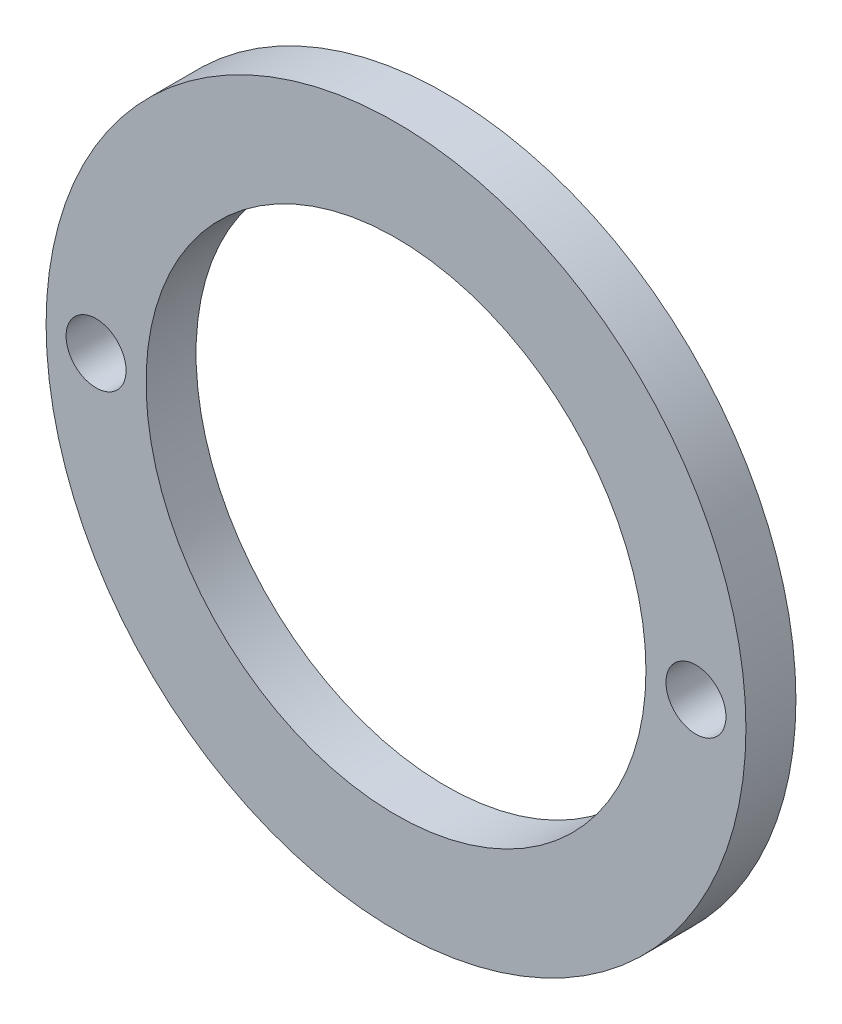
SolidWorks part; units mm, degrees
material "7075-T6 (SN)"
ref_plane "Front Plane" through (0, 0, 0) normal (0, 0, 1) x (1, 0, 0)
ref_plane "Top Plane" through (0, 0, 0) normal (0, 1, 0) x (1, 0, 0)
ref_plane "Right Plane" through (0, 0, 0) normal (1, 0, 0) x (0, 0, -1)
sketch "Sketch1" plane through (0, 0, 0) normal (0, 0, 1) x (1, 0, 0)
  circle A0 centre (0, 0) radius 7
  circle A1 centre (0, 0) radius 5
extrude "M10x0p5_Thin_Retaining_Nut" add sketch "Sketch1" along normal blind 1 from offset 1
sketch "Sketch2" plane through (0, 0, 0) normal (0, 0, 1) x (1, 0, 0)
  circle A0 centre (-6, 0) radius 0.6
  circle A1 centre (6, 0) radius 0.6
extrude "Two_Pin_Wrench_Holes_D1p2" cut sketch "Sketch2" against normal through all
